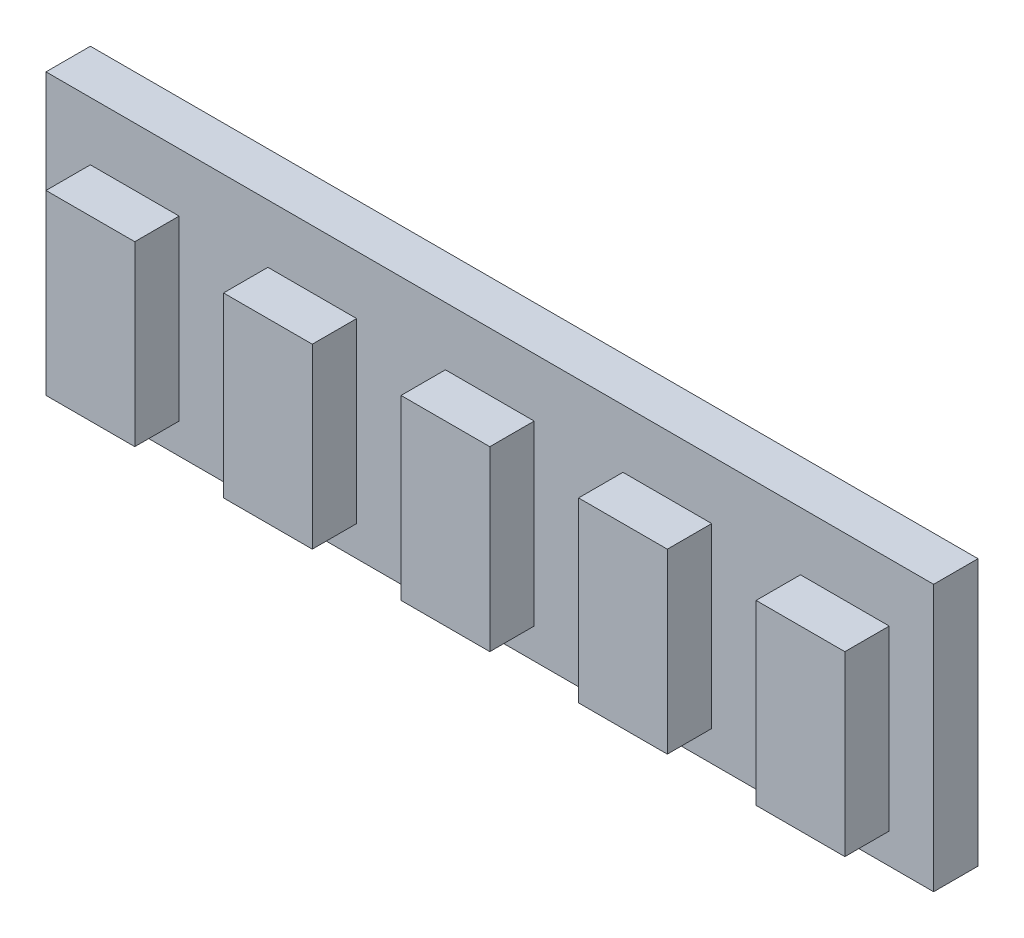
SolidWorks part; units mm, degrees
ref_plane "Front Plane" through (0, 0, 0) normal (0, 0, 1) x (1, 0, 0)
ref_plane "Top Plane" through (0, 0, 0) normal (0, 1, 0) x (1, 0, 0)
ref_plane "Right Plane" through (0, 0, 0) normal (1, 0, 0) x (0, 0, -1)
sketch "Sketch1" plane through (0, 0, 0) normal (0, 0, 1) x (1, 0, 0)
  line L1 (-31.5596, 18.7156) -> (68.4404, 18.7156)
  line L2 (-31.5596, 18.7156) -> (-31.5596, -11.2844)
  line L3 (-31.5596, -11.2844) -> (68.4404, -11.2844)
  line L4 (68.4404, 18.7156) -> (68.4404, -11.2844)
  dimension "D1" = 100
  dimension "D2" = 30
extrude "Boss-Extrude1" add sketch "Sketch1" along normal blind 5
sketch "Sketch2" plane through (0, 0, 5) normal (0, 0, 1) x (1, 0, 0)
  line L0 (-31.5596, 18.7156) -> (-31.5596, -11.2844) construction
  line L1 (-26.5596, 12.1433) -> (-16.5596, 12.1433)
  line L2 (-26.5596, 12.1433) -> (-26.5596, -7.8567)
  line L3 (-26.5596, -7.8567) -> (-16.5596, -7.8567)
  line L4 (-16.5596, 12.1433) -> (-16.5596, -7.8567)
  dimension "D1" = 10
  dimension "D2" = 20
  dimension "D3" = 5
extrude "Boss-Extrude2" add sketch "Sketch2" along normal blind 5
pattern_linear "LPattern1" count 5 spacing 20 along (1, 0, 0) of "Boss-Extrude2"
